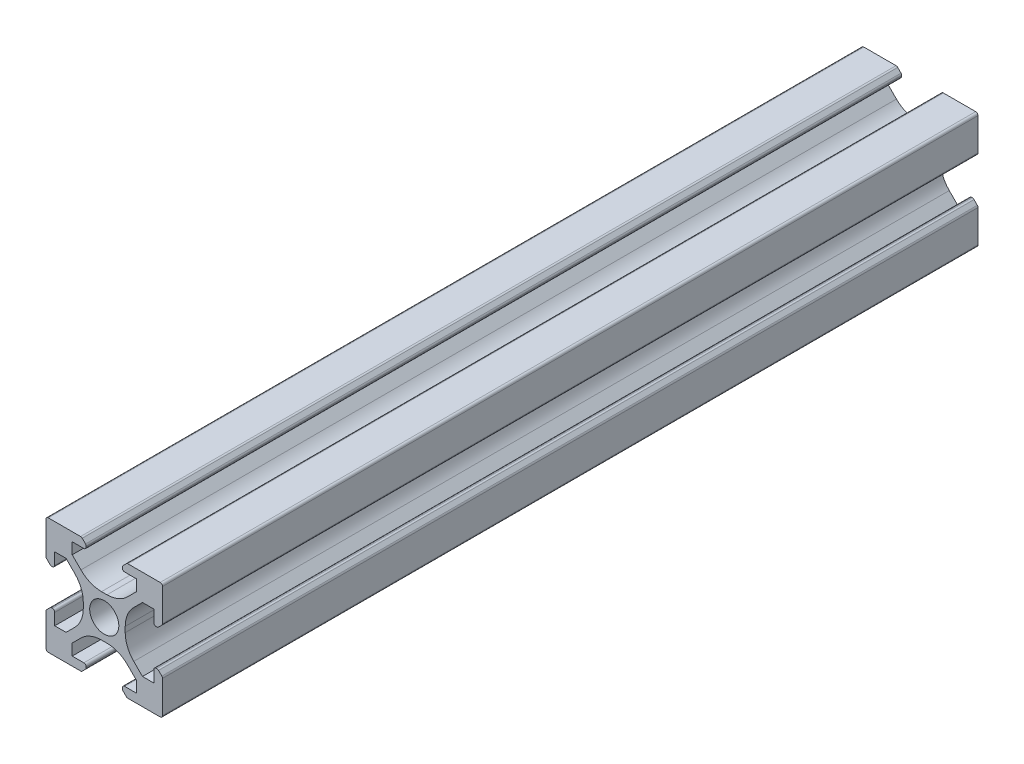
SolidWorks part; units mm, degrees
material "6063-O"
ref_plane "Plano frontal" through (0, 0, 0) normal (0, 0, 1) x (1, 0, 0)
ref_plane "Plano superior" through (0, 0, 0) normal (0, 1, 0) x (1, 0, 0)
ref_plane "Plano direito" through (0, 0, 0) normal (1, 0, 0) x (0, 0, -1)
sketch "Esboço1" plane through (0, 0, 0) normal (0, 0, 1) x (1, 0, 0)
  line L0 (-9.0343, 3.1) -> (-8.9, 3.1)
  line L3 (-10, 10) -> (-4.0657, 10)
  line L5 (-10, -10) -> (10, 10) construction
  line L6 (-10, 10) -> (10, -10) construction
  line L7 (-8.5, 3.5) -> (-8.5, 5.5)
  line L8 (-10, 0) -> (10, 0) construction
  line L9 (0, 10) -> (0, -10) construction
  line L12 (-8.5, 5.5) -> (-6.5607, 5.5)
  line L15 (-6.5607, 5.5) -> (-5.0645, 4.0038)
  line L16 (-3.6, 0.4683) -> (-3.6, 0)
  line L17 (-0.4683, 3.6) -> (0, 3.6)
  line L18 (-5.5, 6.5607) -> (-4.0038, 5.0645)
  line L21 (-5.5, 8.5) -> (-5.5, 6.5607)
  line L24 (-3.5, 8.5) -> (-5.5, 8.5)
  line L25 (-3.1, 9.0343) -> (-3.1, 8.9)
  line L44 (-10, 4.0657) -> (-10, 10)
  line L45 (-9.8828, 3.7828) -> (-9.3172, 3.2172)
  line L46 (-3.7828, 9.8828) -> (-3.2172, 9.3172)
  line L47 (-3.6, 0) -> (-2.5, 0)
  line L48 (0, 3.6) -> (0, 2.5)
  arc A0 (-3.5, 8.5) -> (-3.1, 8.9) centre (-3.5, 8.9) ccw
  arc A1 (-3.7828, 9.8828) -> (-4.0657, 10) centre (-4.0657, 9.6) ccw
  arc A2 (-10, 4.0657) -> (-9.8828, 3.7828) centre (-9.6, 4.0657) ccw
  arc A3 (-8.5, 3.5) -> (-8.9, 3.1) centre (-8.9, 3.5) cw
  arc A4 (-3.2172, 9.3172) -> (-3.1, 9.0343) centre (-3.5, 9.0343) cw
  arc A5 (-9.3172, 3.2172) -> (-9.0343, 3.1) centre (-9.0343, 3.5) ccw
  arc A6 (-3.6, 0.4683) -> (-5.0645, 4.0038) centre (-8.6, 0.4683) ccw
  arc A7 (-4.0038, 5.0645) -> (-0.4683, 3.6) centre (-0.4683, 8.6) ccw
  circle A8 centre (0, 0) radius 2.5
  point P6 (-10, 3.1)
  point P28 (-3.1, 8.5)
  point P31 (-3.1, 10)
  point P33 (-3.9, 10)
  point P36 (-10, 3.9)
  point P39 (-8.5, 3.1)
  point P42 (-3.1, 9.2)
  point P45 (-9.2, 3.1)
  point P48 (-3.6, 2.5393)
  point P51 (-2.5393, 3.6)
  dimension "D5" = 10
  dimension "D9" = 0.4
  dimension "D10" = 0.4
  dimension "D11" = 5
  dimension "D12" = 5
  dimension "D13" = 5
  dimension "D1" = 6.9
  dimension "D2" = 1.5
  dimension "D3" = 3.6
  dimension "D4" = 1.5
  dimension "D6" = 2.4
  dimension "D7" = 3.6
  dimension "D8" = 45
extrude "Ressalto-extrusão1" add sketch "Esboço1" along normal blind 140
sketch "Esboço3" plane through (0, 0, 0) normal (1, 0, 0) x (0, 0, -1)
  line L0 (0, 0) -> (-140, 0) construction
  line L1 (-140, 2.5) -> (-140, 0) construction
pattern_circular "PadrãoCircular1" count 4 every 90 about axis through (0, 0, 0) along (0, 0, 1) of "Ressalto-extrusão1"
fillet "Filete1" radius 0.4 4 edges at (-10, -10, 70) (-10, 10, 70) (10, -10, 70) (10, 10, 70)
ref_plane "Plane1" through (0, 0, 70) normal (0, 0, 1) x (1, 0, 0)
